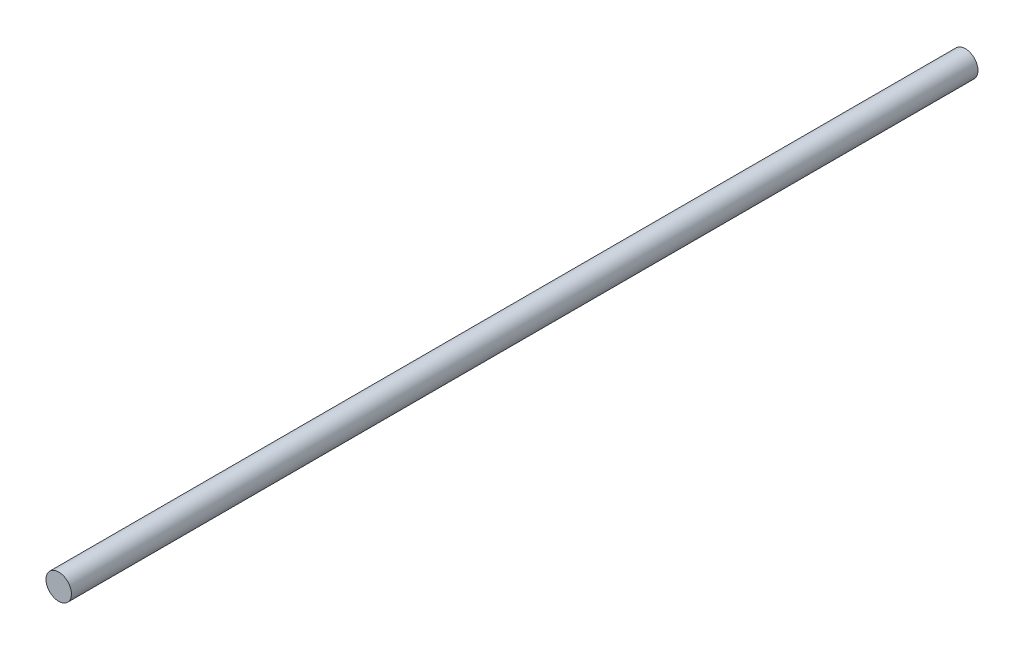
SolidWorks part; units mm, degrees
ref_plane "Plan de face" through (0, 0, 0) normal (0, 0, 1) x (1, 0, 0)
ref_plane "Plan de dessus" through (0, 0, 0) normal (0, 1, 0) x (1, 0, 0)
ref_plane "Plan de droite" through (0, 0, 0) normal (1, 0, 0) x (0, 0, -1)
sketch "Esquisse1" plane through (0, 0, 0) normal (0, 0, 1) x (1, 0, 0)
  circle A0 centre (0, 0) radius 2.105
  dimension "D1" = 4.21
extrude "Boss.-Extru.1" add sketch "Esquisse1" along normal blind 150 contours A0
